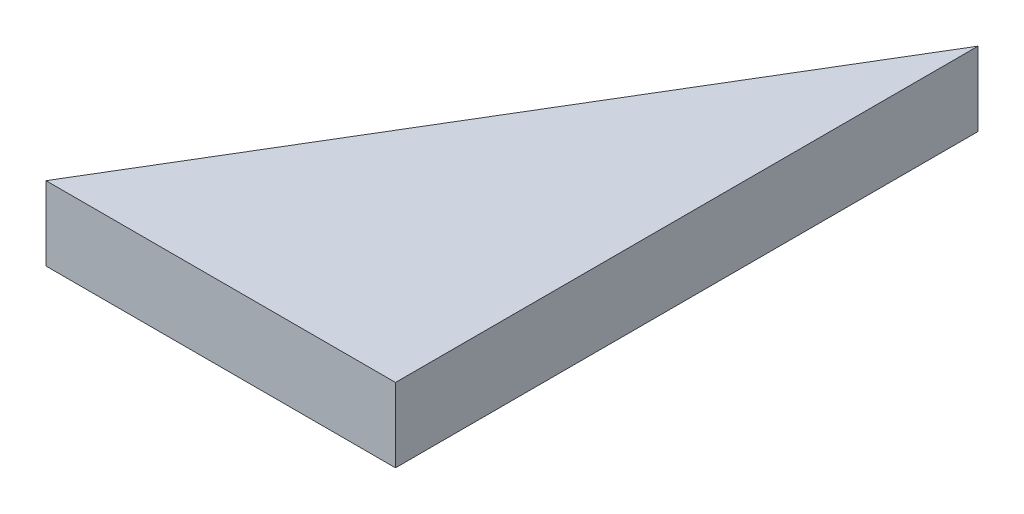
SolidWorks part; units mm, degrees
material "ABS"
ref_plane "Plan de face" through (0, 0, 0) normal (0, 0, 1) x (1, 0, 0)
ref_plane "Plan de dessus" through (0, 0, 0) normal (0, 1, 0) x (1, 0, 0)
ref_plane "Plan de droite" through (0, 0, 0) normal (1, 0, 0) x (0, 0, -1)
sketch "Esquisse1" plane through (0, 0, 0) normal (0, 1, 0) x (1, 0, 0)
  line L0 (-30, 0) -> (0, 0)
  line L1 (0, 0) -> (0, 50)
  line L2 (0, 50) -> (-30, 0)
  line L3 (-55, 0) -> (55, 0) construction
  dimension "D1" = 50
  dimension "D2" = 30
extrude "Boss.-Extru.1" add sketch "Esquisse1" along normal blind 6.35
